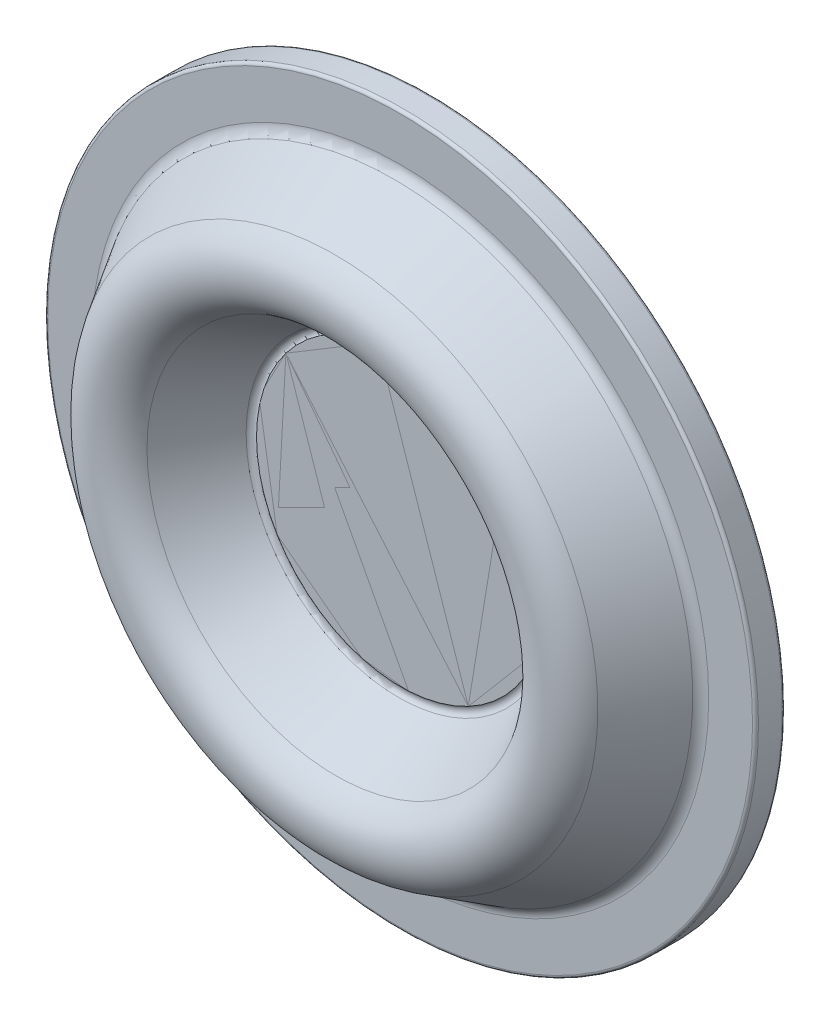
SolidWorks part; units mm, degrees
material "Rubber"
ref_plane "Front Plane" through (0, 0, 0) normal (0, 0, 1) x (1, 0, 0)
ref_plane "Top Plane" through (0, 0, 0) normal (0, 1, 0) x (1, 0, 0)
ref_plane "Right Plane" through (0, 0, 0) normal (1, 0, 0) x (0, 0, -1)
sketch "Sketch1" plane through (0, 0, 0) normal (1, 0, 0) x (0, 0, -1)
  line L0 (0, 57.75) -> (0, 59.25)
  line L1 (-0.5, 59.75) -> (-4.5, 59.75)
  line L2 (-5, 59.25) -> (-5, 51.8794)
  line L3 (-5.9672, 50.1667) -> (-15.9182, 44.1656)
  line L5 (-4.9, 24.25) -> (-4.9, 0)
  line L6 (-4.9, 0) -> (0.1, 0)
  line L7 (0.1, 0) -> (0.1, 21.5)
  line L9 (-15.092, 42.7955) -> (-5.4179, 48.6296)
  line L10 (0, 56.2668) -> (0, 55.8)
  line L11 (-0.8, 55) -> (-2.75, 55)
  line L12 (-3, 54.75) -> (-3, 52.9112)
  line L13 (0.1, 0) -> (0, 0) construction
  line L14 (-15, 33.1503) -> (-2.4394, 25.8984)
  line L15 (-15.8, 31.7646) -> (-5.2357, 25.6653)
  arc A0 (-5, 51.8794) -> (-5.9672, 50.1667) centre (-7, 51.8794) cw
  arc A1 (-15.9182, 44.1656) -> (-15.8, 31.7646) centre (-12.2, 38) ccw
  arc A2 (-5.2357, 25.6653) -> (-4.9, 24.25) centre (-5.7357, 24.7993) cw
  arc A3 (0.1, 21.5) -> (-2.4394, 25.8984) centre (-4.9788, 21.5) ccw
  arc A4 (-15, 33.1503) -> (-15.092, 42.7955) centre (-12.2, 38) cw
  arc A5 (0, 57.75) -> (0, 56.2668) centre (-0.3, 57.0084) cw
  arc A6 (-3, 52.9112) -> (-5.4179, 48.6296) centre (-8, 52.9112) cw
  arc A7 (-3, 54.75) -> (-2.75, 55) centre (-2.75, 54.75) cw
  arc A8 (0, 55.8) -> (-0.8, 55) centre (-0.8, 55.8) cw
  arc A9 (-0.5, 59.75) -> (0, 59.25) centre (-0.5, 59.25) cw
  arc A10 (-5, 59.25) -> (-4.5, 59.75) centre (-4.5, 59.25) cw
  point P38 (-5, 50.75)
  dimension "D1" = 7.2
  dimension "D3" = 1.6
  dimension "D4" = 2
  dimension "D8" = 0.8
  dimension "D10" = 211.093
  dimension "D13" = 0.25
  dimension "D21" = 0.8
  dimension "D22" = 0.5
  dimension "D24" = 5
  dimension "D25" = 30
  dimension "D7" = 5.5
  dimension "D12" = 1
  dimension "D27" = 101.5
  dimension "D5" = 119.5
  dimension "D6" = 110
  dimension "D9" = 115.5
  dimension "D11" = 5
  dimension "D14" = 14.4
  dimension "D16" = 5
  dimension "D17" = 76
  dimension "D18" = 14.5
  dimension "D19" = 43
  dimension "D20" = 48.5
  dimension "D23" = 3
revolve "Revolve1" add sketch "Sketch1" angle 360 about L13
sketch "Sketch2" plane through (0, 0, -0.1) normal (0, 0, -1) x (-1, 0, 0)
  line L0 (0, 0) -> (0, 67.3059) construction
  arc A0 (2.8125, -5.3) -> (-2.8125, -5.3) centre (0, 0) ccw construction
  text T0 "XX/XX/20XX" font "Century Gothic" height 2.5
  dimension "D1" = 12
extrude "Extrude1" add sketch "Sketch2" along normal blind 0.1
sketch "Sketch3" plane through (0, 0, 0) normal (1, 0, 0) x (0, 0, -1)
  line L0 (0, 0) -> (-28.3544, 0) construction
  line L1 (-4.9, 24.25) -> (-4.31, 23.8813)
  line L2 (-2.9, 21.3373) -> (-2.9, 0)
  line L4 (-4.9, 24.25) -> (-4.9, 0) construction
  line L6 (-4.9, 24.25) -> (-4.9, 0)
  line L9 (-2.9, 0) -> (-4.9, 0)
  arc A2 (-4.31, 23.8813) -> (-2.9, 21.3373) centre (-5.9, 21.3373) cw
  point P14 (-2.9, 23)
  dimension "D3" = 3
  dimension "D1" = 2
  dimension "D2" = 46
revolve "Revolve2" add sketch "Sketch3" angle 360 about L0
